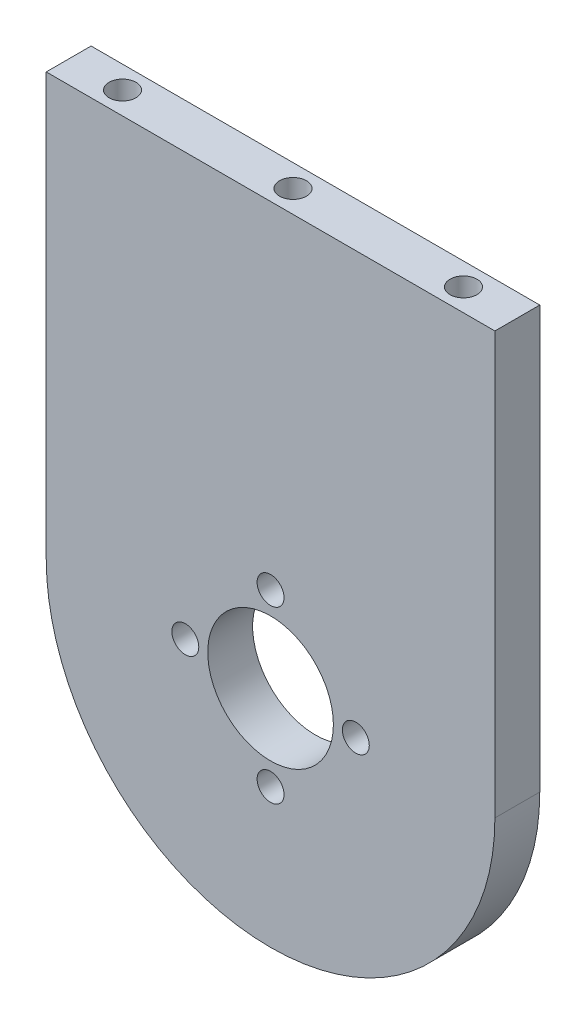
SolidWorks part; units mm, degrees
ref_plane "Plan de face" through (0, 0, 0) normal (0, 0, 1) x (1, 0, 0)
ref_plane "Plan de dessus" through (0, 0, 0) normal (0, 1, 0) x (1, 0, 0)
ref_plane "Plan de droite" through (0, 0, 0) normal (1, 0, 0) x (0, 0, -1)
sketch "Esquisse1" plane through (0, 0, 0) normal (0, 0, 1) x (1, 0, 0)
  line L0 (-47, 47) -> (47, 47)
  line L1 (-47, 47) -> (-47, -46.8078)
  line L2 (47, 47) -> (47, -46.8078)
  line L3 (-47, -46.8078) -> (47, -46.8078)
  circle A1 centre (0, 0) radius 7
extrude "Boss.-Extru.1" add sketch "Esquisse1" along normal blind 5
sketch "Esquisse2" plane through (0, 0, 5) normal (0, 0, 1) x (1, 0, 0)
  line L0 (-25, 0) -> (25, 0)
  line L1 (-25, 0) -> (-25, 50.4793)
  line L2 (25, 0) -> (25, 50.4793)
  line L3 (-25, 50.4793) -> (25, 50.4793)
  circle A0 centre (0, 9.5) radius 1.5
  circle A1 centre (9.5, 0) radius 1.5
  circle A2 centre (0, -9.5) radius 1.5
  circle A3 centre (-9.5, 0) radius 1.5
  circle A6 centre (0, 0) radius 25
  point P4 (0, 0)
  point P12 (0, 0)
  point P33 (0, 0)
  dimension "D1" = 9.5
  dimension "D2" = 4
extrude "Enlèv. mat.-Extru.1" cut sketch "Esquisse2" against normal through all
sketch "Esquisse3" plane through (0, 47, 0) normal (0, 1, 0) x (1, 0, 0)
  line L0 (-25, 0) -> (-25, -5) construction
  line L1 (25, 0) -> (25, -5) construction
  circle A0 centre (0, -2.5) radius 1.5
  circle A2 centre (-19, -2.5) radius 1.5
  circle A3 centre (19, -2.5) radius 1.5
  dimension "D1" = 2.5
  dimension "D2" = 6
  dimension "D3" = 6
extrude "Enlèv. mat.-Extru.2" cut sketch "Esquisse3" against normal blind 10
